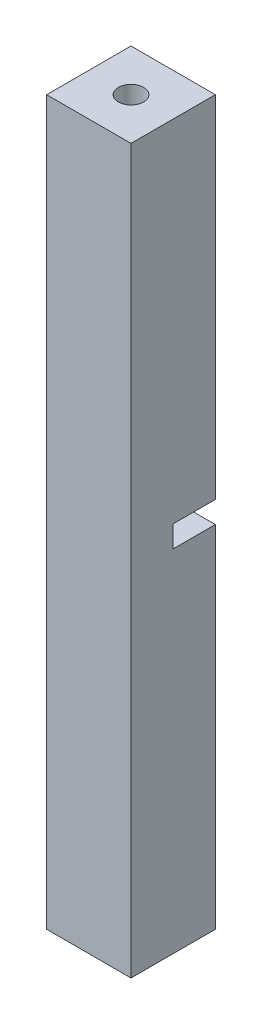
SolidWorks part; units mm, degrees
ref_plane "Front Plane" through (0, 0, 0) normal (0, 0, 1) x (1, 0, 0)
ref_plane "Top Plane" through (0, 0, 0) normal (0, 1, 0) x (1, 0, 0)
ref_plane "Right Plane" through (0, 0, 0) normal (1, 0, 0) x (0, 0, -1)
sketch "Sketch1" plane through (0, 0, 0) normal (0, 1, 0) x (1, 0, 0)
  circle A0 centre (0, 0) radius 3.5
  circle A1 centre (0, 0) radius 1.05
  dimension "D1" = 7
  dimension "D2" = 2.1
extrude "Boss-Extrude1" add sketch "Sketch1" along normal blind 60
sketch "Sketch3" plane through (0, 60, 0) normal (0, 1, 0) x (1, 0, 0)
  circle A0 centre (0, 0) radius 3.05
  dimension "D1" = 6.1
extrude "Cut-Extrude1" cut sketch "Sketch3" along normal blind 0.9 and the other way blind 0.9 from offset 30 offset against normal yes
sketch "Sketch4" plane through (0, 60, 0) normal (0, 1, 0) x (1, 0, 0)
  line L0 (-4.2667, 0) -> (4.2667, 0)
  arc A0 (4.2667, 0) -> (-4.2667, 0) centre (0, 0) ccw
extrude "Cut-Extrude2" cut sketch "Sketch4" against normal blind 0.9 and the other way blind 0.9 from offset 30 offset against normal yes
sketch "Sketch5" plane through (0, 0, 0) normal (0, -1, 0) x (1, 0, 0)
  line L1 (-3.5, 3.5) -> (3.5, 3.5)
  line L2 (-3.5, 3.5) -> (-3.5, -3.5)
  line L3 (-3.5, -3.5) -> (3.5, -3.5)
  line L4 (3.5, 3.5) -> (3.5, -3.5)
  line L5 (-3.5, 3.5) -> (3.5, -3.5) construction
  line L6 (-3.5, -3.5) -> (3.5, 3.5) construction
  circle A0 centre (0, 0) radius 3.5 construction
  circle A1 centre (0, 0) radius 1.05
  point P0 (0, 0)
extrude "Boss-Extrude2" add sketch "Sketch5" against normal up to surface (60 mm away) up to face at (0, 60, 3.5)
sketch "Sketch6" plane through (0, 60, 0) normal (0, 1, 0) x (1, 0, 0)
  circle A0 centre (0, 0) radius 3.05
  point P2 (0, 0)
extrude "Cut-Extrude3" cut sketch "Sketch6" against normal blind 0.9 and the other way blind 0.9 from offset 30 offset against normal yes
sketch "Sketch7" plane through (0, 60, 0) normal (0, 1, 0) x (1, 0, 0)
  line L0 (-4.2667, 0) -> (4.2667, 0)
  line L3 (-4.2667, 0) -> (-4.2667, 4.2744)
  line L4 (-4.2667, 4.2744) -> (4.2667, 4.2744)
  line L5 (4.2667, 0) -> (4.2667, 4.2744)
  line L6 (0, 0) -> (4.2667, 4.2744) construction
  line L7 (-4.2667, 4.2744) -> (0, 0) construction
extrude "Cut-Extrude4" cut sketch "Sketch7" against normal blind 0.9 and the other way blind 0.9 from offset 30 offset against normal yes
